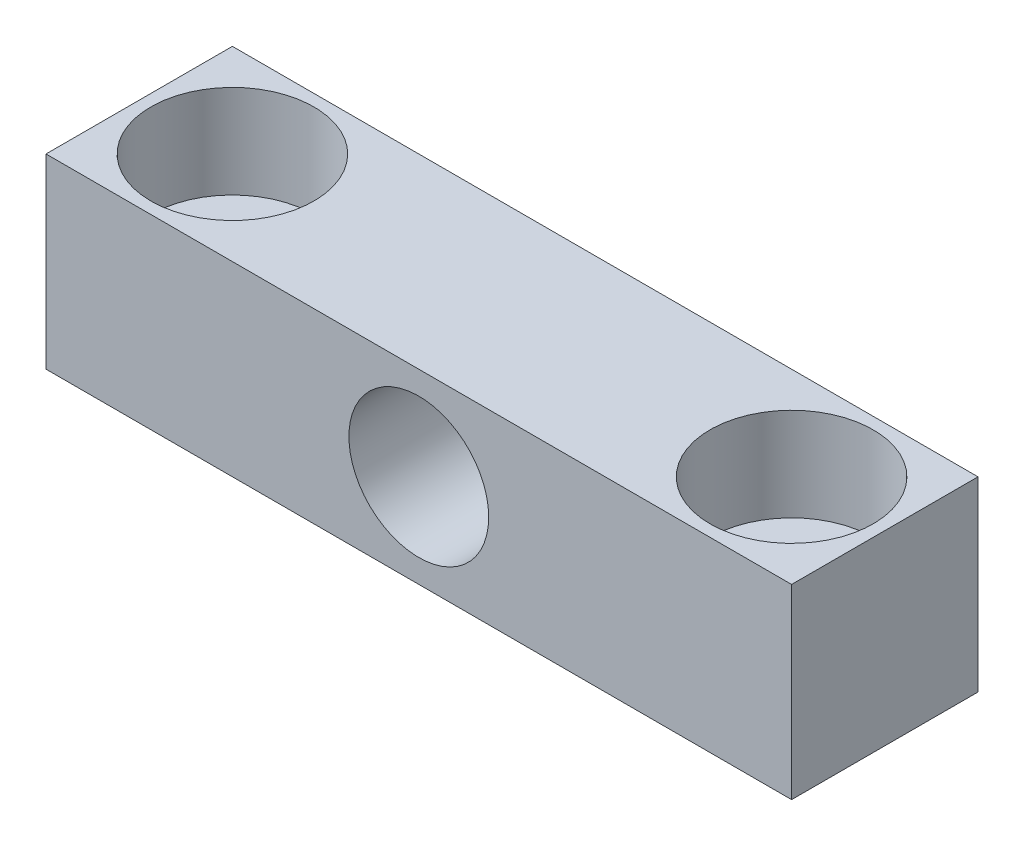
SolidWorks part; units mm, degrees
ref_plane "Front Plane" through (0, 0, 0) normal (0, 0, 1) x (1, 0, 0)
ref_plane "Top Plane" through (0, 0, 0) normal (0, 1, 0) x (1, 0, 0)
ref_plane "Right Plane" through (0, 0, 0) normal (1, 0, 0) x (0, 0, -1)
sketch "Sketch1" plane through (0, 0, 0) normal (0, 1, 0) x (1, 0, 0)
  line L0 (-25.4, 6.35) -> (25.4, -6.35) construction
  line L1 (-25.4, 6.35) -> (25.4, 6.35)
  line L2 (-25.4, 6.35) -> (-25.4, -6.35)
  line L3 (-25.4, -6.35) -> (25.4, -6.35)
  line L4 (25.4, 6.35) -> (25.4, -6.35)
  dimension "D1" = 12.7
  dimension "D2" = 50.8
extrude "Extrude1" add sketch "Sketch1" along normal blind 12.7
sketch "Sketch3" plane through (0, 0, 6.35) normal (0, 0, 1) x (1, 0, 0)
  line L0 (0, 12.7) -> (0, 0) construction
  line L1 (-25.4, 12.7) -> (25.4, 12.7) construction
  line L2 (-25.4, 0) -> (25.4, 0) construction
  circle A0 centre (0, 6.35) radius 4.7625
  dimension "D1" = 9.525
extrude "Cut-Extrude2" cut sketch "Sketch3" against normal through all
hole_wizard "CBORE for 1/4 Socket Head Cap Screw1" positions "Sketch5" profile "Sketch4" counterbore size "1/4" standard "Ansi Inch" end condition through all
sketch "Sketch5" plane through (0, 12.7, 0) normal (0, 1, 0) x (-1, 0, 0)
  line L1 (25.4, 0) -> (-25.4, 0) construction
  line L2 (25.4, -6.35) -> (25.4, 6.35) construction
  line L3 (-25.4, 6.35) -> (-25.4, -6.35) construction
  line L4 (0, -6.35) -> (0, 6.35) construction
  line L5 (-25.4, -6.35) -> (25.4, -6.35) construction
  line L6 (25.4, 6.35) -> (-25.4, 6.35) construction
  point P0 (-19.05, 0)
  point P1 (19.05, 0)
  dimension "D1" = 38.1
sketch "Sketch4" plane through (19.05, 12.7, 0) normal (1, 0, 0) x (0, 0, 1)
  line L0 (0, 0) -> (0, 12.7)
  line L1 (0, 12.7) -> (3.3782, 12.7)
  line L3 (3.3782, 12.7) -> (3.3782, 6.35)
  line L4 (3.3782, 6.35) -> (5.5562, 6.35)
  line L5 (5.5562, 6.35) -> (5.5562, 0)
  line L7 (5.5562, 0) -> (0, 0)
  line L11 (0, -6.35) -> (0, 107.95) construction
  dimension "Thru Hole Dia." = 6.7564
  dimension "Thru Hole Depth" = 12.7
  dimension "C'Bore Dia." = 11.1125
  dimension "C'Bore Depth" = 6.35
